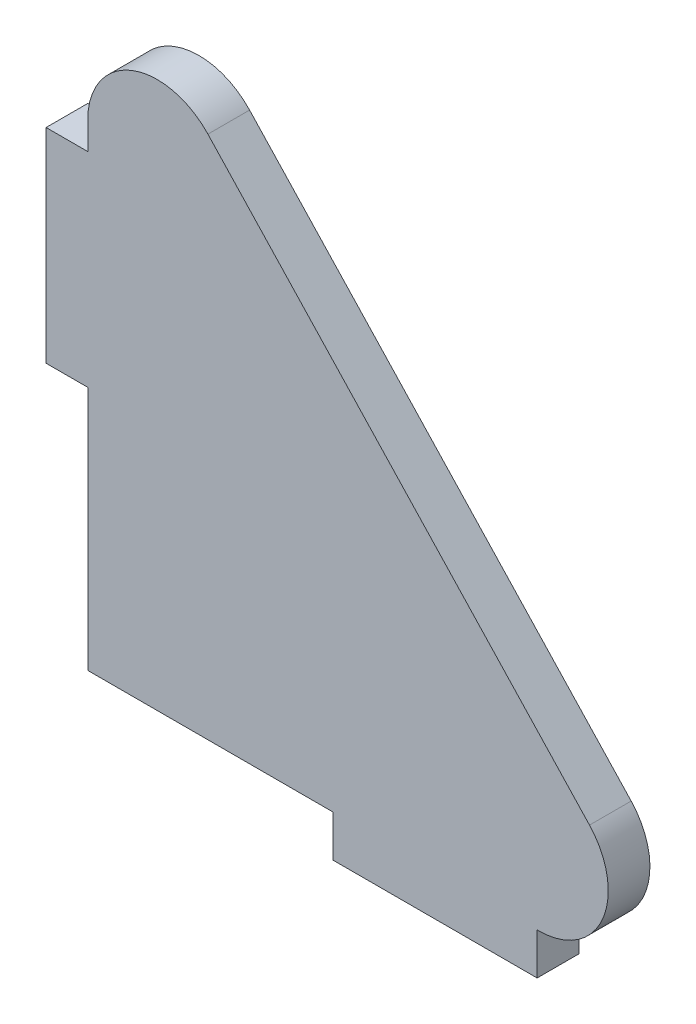
SolidWorks part; units mm, degrees
ref_plane "Plan de face" through (0, 0, 0) normal (0, 0, 1) x (1, 0, 0)
ref_plane "Plan de dessus" through (0, 0, 0) normal (0, 1, 0) x (1, 0, 0)
ref_plane "Plan de droite" through (0, 0, 0) normal (1, 0, 0) x (0, 0, -1)
sketch "Sketch1" plane through (0, 0, 0) normal (0, 0, 1) x (1, 0, 0)
  line L0 (-10.1073, 16.9794) -> (-10.1073, -30.0206)
  line L1 (-10.1073, -30.0206) -> (33.8927, -30.0206)
  line L2 (33.8927, -30.0206) -> (-10.1073, 16.9794)
  line L3 (-10.1073, -30.0206) -> (16.4389, -3.4744) construction
  line L4 (7.5427, -30.0206) -> (22.2427, -30.0206)
  line L5 (7.5427, -30.0206) -> (7.5427, -33.0206)
  line L6 (7.5427, -33.0206) -> (22.2427, -33.0206)
  line L7 (22.2427, -30.0206) -> (22.2427, -33.0206)
  line L8 (-10.1073, 2.3294) -> (-13.1073, 2.3294)
  line L9 (-13.1073, -12.3706) -> (-13.1073, 2.3294)
  line L10 (-10.1073, -12.3706) -> (-13.1073, -12.3706)
  line L11 (-10.1073, -12.3706) -> (-10.1073, 2.3294)
  point P7 (14.8927, -33.0206)
  dimension "D1" = 47
  dimension "D2" = 44
  dimension "D3" = 3
  dimension "D4" = 14.7
  dimension "D5" = 25
  dimension "D6" = 45
extrude "Boss-Extrude1" add sketch "Sketch1" along normal blind 3 contours L3 L1 L2 | L7 L1 L5 L6 | L0 L3 L2 | L10 L0 L8 L9
fillet "Fillet1" radius 5 2 edges at (33.8927, -30.0206, 1.5) (-10.1073, 16.9794, 1.5)
